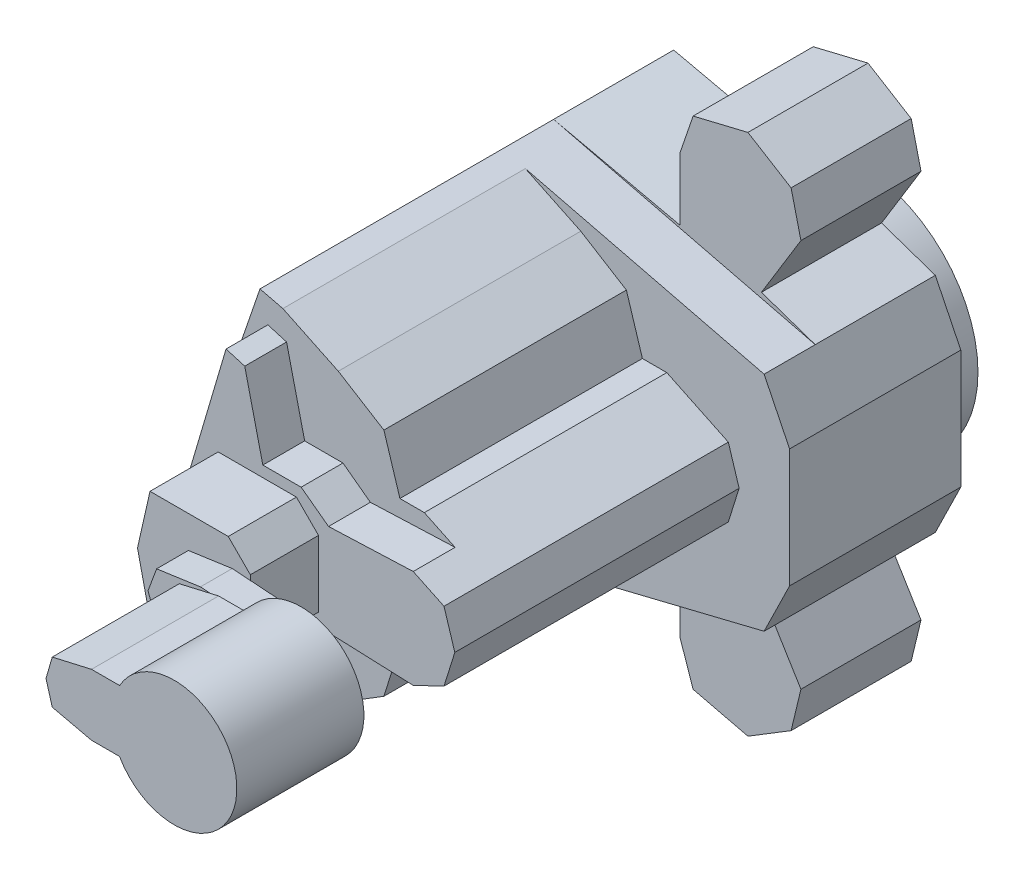
SolidWorks part; units mm, degrees
ref_plane "Front Plane" through (0, 0, 0) normal (0, 0, 1) x (1, 0, 0)
ref_plane "Top Plane" through (0, 0, 0) normal (0, 1, 0) x (1, 0, 0)
ref_plane "Right Plane" through (0, 0, 0) normal (1, 0, 0) x (0, 0, -1)
sketch "Sketch1" plane through (0, 0, 0) normal (0, 0, 1) x (1, 0, 0)
  line L0 (-220.0638, 0) -> (-198.9079, -153.1283)
  line L1 (-198.9079, -153.1283) -> (-173.7223, -226.6701)
  line L2 (-173.7223, -226.6701) -> (-10.5198, -189.8992)
  line L3 (-10.5198, -189.8992) -> (-10.5198, -270.9967)
  line L4 (-10.5198, -270.9967) -> (6.4172, -320.4528)
  line L5 (6.4172, -320.4528) -> (77.1259, -337.4866)
  line L6 (77.1259, -337.4866) -> (132.8571, -303.3941)
  line L7 (132.8571, -303.3941) -> (145.5301, -250.7874)
  line L8 (145.5301, -250.7874) -> (94.5723, -167.4866)
  line L9 (94.5723, -167.4866) -> (164.0148, -143.7049)
  line L10 (164.0148, -143.7049) -> (180.0769, -110.9114)
  line L11 (180.0769, -110.9114) -> (196.9001, -76.5641)
  line L12 (196.9001, -76.5641) -> (196.9001, 0)
  line L13 (196.9001, 0) -> (-220.0638, 0)
extrude "Boss-Extrude1" add sketch "Sketch1" along normal blind 155
sketch "Sketch2" plane through (0, 0, 155) normal (0, 0, 1) x (1, 0, 0)
  line L0 (-220.0638, 0) -> (-198.9079, -153.1283)
  line L1 (-198.9079, -153.1283) -> (-173.7223, -226.6701)
  line L2 (-173.7223, -226.6701) -> (164.0148, -143.7049)
  line L3 (164.0148, -143.7049) -> (196.9001, -76.5641)
  line L4 (196.9001, -76.5641) -> (196.9001, 0)
  line L5 (196.9001, 0) -> (-220.0638, 0)
extrude "Boss-Extrude2" add sketch "Sketch2" along normal blind 66
sketch "Sketch3" plane through (0, 0, 221) normal (0, 0, 1) x (1, 0, 0)
  line L0 (-220.0638, 0) -> (-198.9079, -153.1283)
  line L1 (-198.9079, -153.1283) -> (-173.7223, -226.6701)
  line L2 (-173.7223, -226.6701) -> (-144.1886, -219.4151)
  line L3 (-173.7223, -226.6701) -> (164.0148, -143.7049) construction
  line L4 (-144.1886, -219.4151) -> (-72.6439, -185.1875)
  line L5 (-72.6439, -185.1875) -> (-13.7846, -148.8316)
  line L6 (-13.7846, -148.8316) -> (0, -104.7451)
  line L7 (0, -104.7451) -> (6.9109, -82.6424)
  line L8 (6.9109, -82.6424) -> (38.4197, -82.6424)
  line L9 (38.4197, -82.6424) -> (117.796, -44.668)
  line L10 (117.796, -44.668) -> (131.7624, 0)
  line L11 (196.9001, 0) -> (-220.0638, 0) construction
  line L12 (131.7624, 0) -> (-220.0638, 0)
extrude "Boss-Extrude3" add sketch "Sketch3" along normal blind 313
sketch "Sketch4" plane through (0, 0, 534) normal (0, 0, 1) x (1, 0, 0)
  line L0 (-220.0638, 0) -> (-163.5141, -191.5767)
  line L1 (-163.5141, -191.5767) -> (-139.4115, -184.462)
  line L2 (-139.4115, -184.462) -> (-116.0597, -85.5614)
  line L3 (-116.0597, -85.5614) -> (-66.5859, -85.5614)
  line L4 (-66.5859, -85.5614) -> (-31.2475, -59.31)
  line L5 (-31.2475, -59.31) -> (78.1079, -63.6552)
  line L6 (38.4197, -82.6424) -> (117.796, -44.668) construction
  line L7 (78.1079, -63.6552) -> (117.796, -44.668)
  line L8 (117.796, -44.668) -> (131.7624, 0)
  line L9 (131.7624, 0) -> (-220.0638, 0)
extrude "Boss-Extrude4" add sketch "Sketch4" along normal blind 54
sketch "Sketch5" plane through (0, 0, 588) normal (0, 0, 1) x (1, 0, 0)
  line L0 (-189.8308, 0) -> (-173.6761, -71.426)
  line L1 (131.7624, 0) -> (-220.0638, 0) construction
  line L2 (-173.6761, -71.426) -> (-72.7091, -71.426)
  line L3 (-72.7091, -71.426) -> (-44.1507, -42.8676)
  line L4 (-44.1507, -42.8676) -> (-44.1507, 0)
  line L5 (-44.1507, 0) -> (-189.8308, 0)
extrude "Boss-Extrude5" add sketch "Sketch5" along normal blind 88
sketch "Sketch6" plane through (0, 0, 676) normal (0, 0, 1) x (1, 0, 0)
  line L0 (-135.2434, 0) -> (-124.137, -30.0296)
  line L1 (-44.1507, 0) -> (-189.8308, 0) construction
  line L2 (-124.137, -30.0296) -> (-67.5956, -38.1069)
  line L3 (-67.5956, -38.1069) -> (-9.9821, -34.0683)
  line L4 (-11.1748, 0) -> (-135.2434, 0)
  arc A0 (-9.9821, -34.0683) -> (-11.1748, 0) centre (476.0158, 0) cw
extrude "Boss-Extrude6" add sketch "Sketch6" along normal blind 41
sketch "Sketch7" plane through (0, 0, 717) normal (0, 0, 1) x (1, 0, 0)
  line L0 (-102.934, 0) -> (-94.8566, -28.0102)
  line L1 (-11.1748, 0) -> (-135.2434, 0) construction
  line L2 (-94.8566, -28.0102) -> (-44.1507, -39.6655)
  line L3 (-44.1507, -42.8676) -> (-44.1507, -36.4635) construction
  line L4 (-44.1507, -39.6655) -> (-7.9617, -39.6655)
  line L5 (131.7624, 0) -> (-44.1507, 0) construction
  line L6 (-102.934, 0) -> (-7.9617, 0)
  line L7 (-7.9617, 0) -> (143.4068, 0)
  arc A1 (-7.9617, -39.6655) -> (143.4068, 0) centre (62.5255, 0) ccw
extrude "Boss-Extrude7" add sketch "Sketch7" along normal blind 164
sketch "Sketch8" plane through (0, 0, 0) normal (0, 0, -1) x (-1, 0, 0)
  line L0 (-196.9001, 0) -> (220.0638, 0) construction
  line L1 (-156.1033, 0) -> (156.1033, 0)
  arc A0 (156.1033, 0) -> (-156.1033, 0) centre (0, 0) cw
extrude "Boss-Extrude8" add sketch "Sketch8" along normal blind 63
mirror "Mirror1" about plane through (196.9001, 0, 155) normal (0, -1, 0) of "Boss-Extrude8", "Boss-Extrude7", "Boss-Extrude6", "Boss-Extrude5", "Boss-Extrude4", "Boss-Extrude3", "Boss-Extrude2", "Boss-Extrude1"
